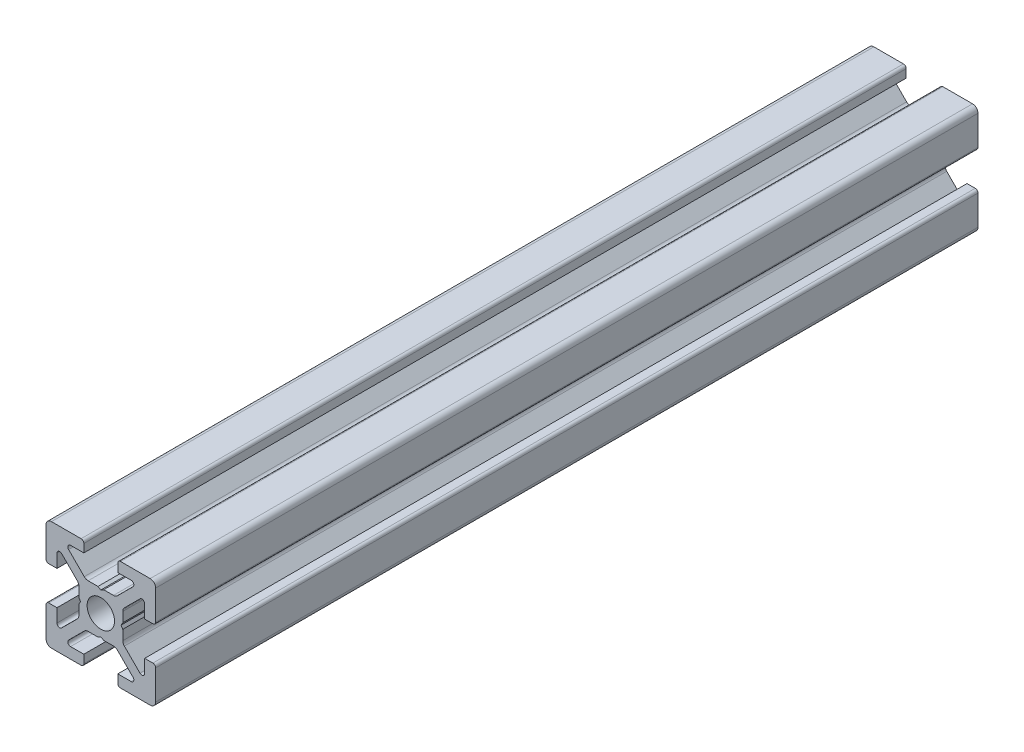
SolidWorks part; units mm, degrees
ref_plane "前视基准面" through (0, 0, 0) normal (0, 0, 1) x (1, 0, 0)
ref_plane "上视基准面" through (0, 0, 0) normal (0, 1, 0) x (1, 0, 0)
ref_plane "右视基准面" through (0, 0, 0) normal (1, 0, 0) x (0, 0, -1)
sketch "草图1" plane through (0, 0, 0) normal (0, 0, 1) x (1, 0, 0)
  line L0 (16.4868, 27.1233) -> (19.3403, 24.2698)
  line L1 (20.1939, 24.6233) -> (20.1939, 27.0434)
  line L2 (20.1939, 27.0434) -> (21.6939, 27.0434)
  line L3 (15.8939, 30.1434) -> (16.1939, 29.6238)
  line L4 (12.1939, 33.8434) -> (12.7135, 34.1434)
  line L5 (22.1939, 26.5434) -> (22.1939, 21.1434)
  line L6 (21.1939, 20.1434) -> (15.7939, 20.1434)
  line L7 (12.1939, 33.8434) -> (11.6743, 34.1434)
  line L8 (12.7135, 34.1434) -> (14.5069, 34.1434)
  line L9 (15.2939, 20.6434) -> (15.2939, 22.1434)
  line L10 (15.2939, 22.1434) -> (17.714, 22.1434)
  line L11 (18.0675, 22.997) -> (15.214, 25.8506)
  line L12 (14.5069, 26.1434) -> (12.7135, 26.1434)
  line L13 (9.1738, 25.8506) -> (6.3202, 22.997)
  line L14 (6.6738, 22.1434) -> (9.0939, 22.1434)
  line L15 (9.0939, 22.1434) -> (9.0939, 20.6434)
  line L16 (15.8939, 30.1434) -> (16.1939, 30.6631)
  line L17 (12.1939, 26.4434) -> (11.6743, 26.1434)
  line L18 (8.5939, 20.1434) -> (3.1939, 20.1434)
  line L19 (2.1939, 21.1434) -> (2.1939, 26.5434)
  line L20 (12.1939, 26.4434) -> (12.7135, 26.1434)
  line L21 (8.4939, 30.1434) -> (8.1939, 30.6631)
  line L22 (2.6939, 27.0434) -> (4.1939, 27.0434)
  line L23 (4.1939, 27.0434) -> (4.1939, 24.6233)
  line L24 (5.0474, 24.2698) -> (7.901, 27.1233)
  line L25 (8.1939, 27.8305) -> (8.1939, 29.6238)
  line L26 (7.901, 33.1635) -> (5.0474, 36.0171)
  line L27 (4.1939, 35.6635) -> (4.1939, 33.2434)
  line L28 (4.1939, 33.2434) -> (2.6939, 33.2434)
  line L29 (8.4939, 30.1434) -> (8.1939, 29.6238)
  line L30 (16.1939, 29.6238) -> (16.1939, 27.8305)
  line L31 (2.1939, 33.7434) -> (2.1939, 39.1434)
  line L32 (3.1939, 40.1434) -> (8.5939, 40.1434)
  line L33 (11.6743, 26.1434) -> (9.8809, 26.1434)
  line L34 (8.1939, 30.6631) -> (8.1939, 32.4564)
  line L35 (9.0939, 39.6434) -> (9.0939, 38.1434)
  line L36 (9.0939, 38.1434) -> (6.6738, 38.1434)
  line L37 (6.3202, 37.2899) -> (9.1738, 34.4363)
  line L38 (9.8809, 34.1434) -> (11.6743, 34.1434)
  line L39 (15.214, 34.4363) -> (18.0675, 37.2899)
  line L40 (17.714, 38.1434) -> (15.2939, 38.1434)
  line L41 (15.2939, 38.1434) -> (15.2939, 39.6434)
  line L44 (15.7939, 40.1434) -> (21.1939, 40.1434)
  line L45 (22.1939, 39.1434) -> (22.1939, 33.7434)
  line L48 (21.6939, 33.2434) -> (20.1939, 33.2434)
  line L49 (20.1939, 33.2434) -> (20.1939, 35.6635)
  line L50 (19.3403, 36.0171) -> (16.4868, 33.1635)
  line L51 (16.1939, 32.4564) -> (16.1939, 30.6631)
  circle A0 centre (12.1939, 30.1434) radius 2.5
  arc A1 (16.1939, 27.8305) -> (16.4868, 27.1233) centre (17.1939, 27.8305) ccw
  arc A2 (19.3403, 24.2698) -> (20.1939, 24.6233) centre (19.6939, 24.6233) ccw
  arc A3 (21.1939, 20.1434) -> (22.1939, 21.1434) centre (21.1939, 21.1434) ccw
  arc A4 (17.714, 22.1434) -> (18.0675, 22.997) centre (17.714, 22.6434) ccw
  arc A5 (15.214, 25.8506) -> (14.5069, 26.1434) centre (14.5069, 25.1434) ccw
  arc A6 (9.8809, 26.1434) -> (9.1738, 25.8506) centre (9.8809, 25.1434) ccw
  arc A7 (6.3202, 22.997) -> (6.6738, 22.1434) centre (6.6738, 22.6434) ccw
  arc A8 (2.1939, 21.1434) -> (3.1939, 20.1434) centre (3.1939, 21.1434) ccw
  arc A9 (4.1939, 24.6233) -> (5.0474, 24.2698) centre (4.6939, 24.6233) ccw
  arc A10 (7.901, 27.1233) -> (8.1939, 27.8305) centre (7.1939, 27.8305) ccw
  arc A11 (8.1939, 32.4564) -> (7.901, 33.1635) centre (7.1939, 32.4564) ccw
  arc A12 (5.0474, 36.0171) -> (4.1939, 35.6635) centre (4.6939, 35.6635) ccw
  arc A13 (3.1939, 40.1434) -> (2.1939, 39.1434) centre (3.1939, 39.1434) ccw
  arc A14 (6.6738, 38.1434) -> (6.3202, 37.2899) centre (6.6738, 37.6434) ccw
  arc A15 (9.1738, 34.4363) -> (9.8809, 34.1434) centre (9.8809, 35.1434) ccw
  arc A16 (14.5069, 34.1434) -> (15.214, 34.4363) centre (14.5069, 35.1434) ccw
  arc A17 (18.0675, 37.2899) -> (17.714, 38.1434) centre (17.714, 37.6434) ccw
  arc A18 (22.1939, 39.1434) -> (21.1939, 40.1434) centre (21.1939, 39.1434) ccw
  arc A19 (20.1939, 35.6635) -> (19.3403, 36.0171) centre (19.6939, 35.6635) ccw
  arc A20 (16.4868, 33.1635) -> (16.1939, 32.4564) centre (17.1939, 32.4564) ccw
  arc A21 (15.7939, 20.1434) -> (15.2939, 20.6434) centre (15.7939, 20.6434) cw
  arc A22 (9.0939, 20.6434) -> (8.5939, 20.1434) centre (8.5939, 20.6434) cw
  arc A23 (2.1939, 26.5434) -> (2.6939, 27.0434) centre (2.6939, 26.5434) cw
  arc A24 (2.6939, 33.2434) -> (2.1939, 33.7434) centre (2.6939, 33.7434) cw
  arc A25 (22.1939, 26.5434) -> (21.6939, 27.0434) centre (21.6939, 26.5434) ccw
  arc A26 (21.6939, 33.2434) -> (22.1939, 33.7434) centre (21.6939, 33.7434) ccw
  arc A27 (15.7939, 40.1434) -> (15.2939, 39.6434) centre (15.7939, 39.6434) ccw
  arc A28 (9.0939, 39.6434) -> (8.5939, 40.1434) centre (8.5939, 39.6434) ccw
  dimension "D1" = 0.5
  dimension "D2" = 4
extrude "凸台-拉伸1" add sketch "草图1" along normal blind 150
